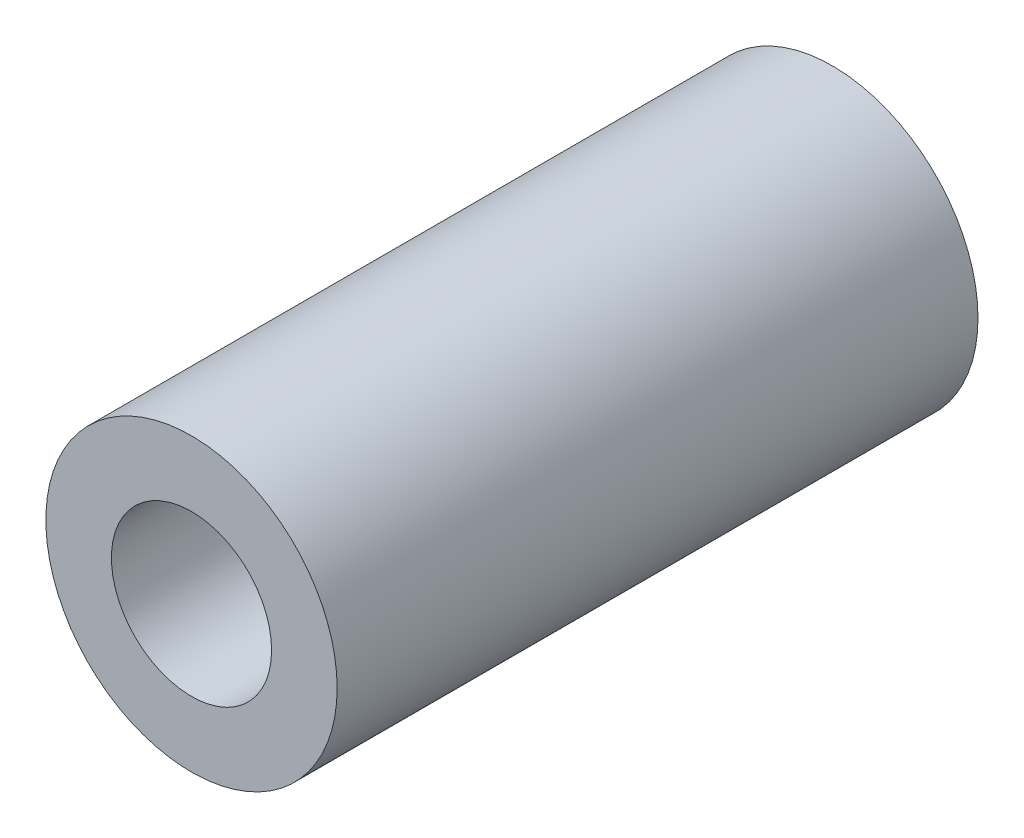
SolidWorks part; units mm, degrees
ref_plane "Front Plane" through (0, 0, 0) normal (0, 0, 1) x (1, 0, 0)
ref_plane "Top Plane" through (0, 0, 0) normal (0, 1, 0) x (1, 0, 0)
ref_plane "Right Plane" through (0, 0, 0) normal (1, 0, 0) x (0, 0, -1)
sketch "Sketch1" plane through (0, 0, 0) normal (0, 0, 1) x (1, 0, 0)
  circle A0 centre (0, 0) radius 2.75
  circle A1 centre (0, 0) radius 5
  dimension "D1" = 5.5
  dimension "D2" = 10
extrude "Boss-Extrude1" add sketch "Sketch1" along normal blind 22
